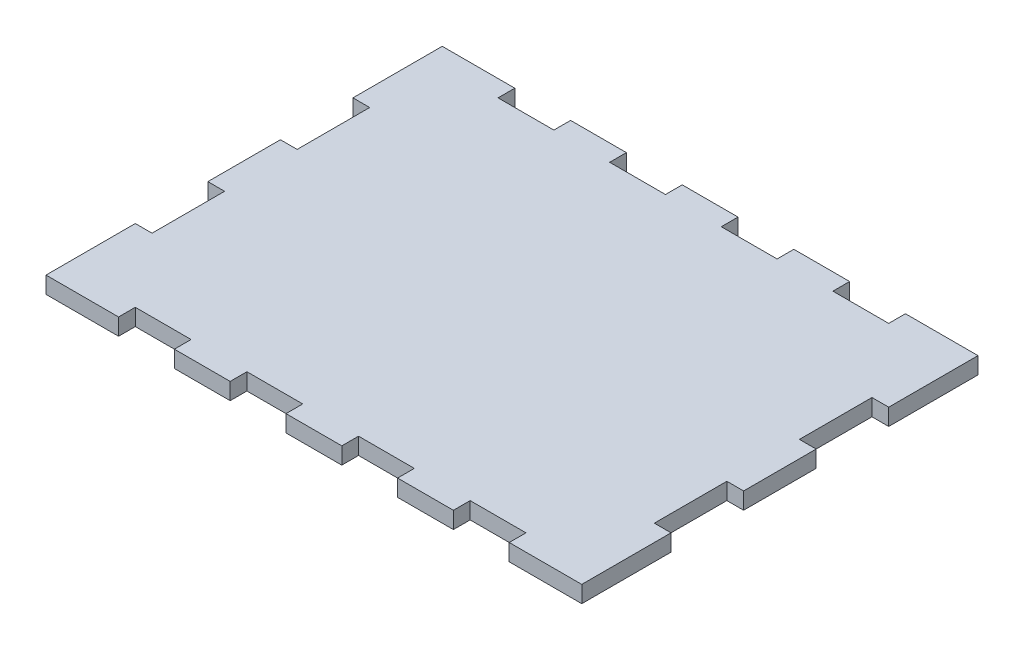
SolidWorks part; units mm, degrees
ref_plane "Front Plane" through (0, 0, 0) normal (0, 0, 1) x (1, 0, 0)
ref_plane "Top Plane" through (0, 0, 0) normal (0, 1, 0) x (1, 0, 0)
ref_plane "Right Plane" through (0, 0, 0) normal (1, 0, 0) x (0, 0, -1)
sketch "Sketch1" plane through (0, 0, 0) normal (0, 1, 0) x (1, 0, 0)
  line L0 (-70, 71) -> (-70, 65)
  line L1 (-96, -71) -> (-70, -71)
  line L2 (-96, -71) -> (-96, -39)
  line L3 (-96, 71) -> (-70, 71)
  line L4 (96, -71) -> (96, -39)
  line L5 (-96, -71) -> (96, 71) construction
  line L6 (-96, 71) -> (96, -71) construction
  line L11 (-90, -66.5625) -> (90, 66.5625) construction
  line L12 (-90, 66.5625) -> (90, -66.5625) construction
  line L13 (-90, -65) -> (-87.8873, -65)
  line L14 (-90, -39) -> (-90, -13)
  line L15 (-90, 65) -> (-87.8873, 65)
  line L16 (90, -39) -> (90, -13)
  line L17 (-90, -65) -> (90, 65) construction
  line L18 (-90, 65) -> (90, -65) construction
  line L19 (-50, 71) -> (-50, 65)
  line L20 (-30, 71) -> (-30, 65)
  line L21 (-10, 71) -> (-10, 65)
  line L22 (10, 71) -> (10, 65)
  line L23 (30, 71) -> (30, 65)
  line L24 (50, 71) -> (50, 65)
  line L25 (70, 71) -> (70, 65)
  line L26 (-50, 71) -> (-30, 71)
  line L27 (-10, 71) -> (10, 71)
  line L28 (30, 71) -> (50, 71)
  line L29 (70, 71) -> (96, 71)
  line L30 (-70, 65) -> (-50, 65)
  line L31 (-30, 65) -> (-10, 65)
  line L32 (10, 65) -> (30, 65)
  line L33 (50, 65) -> (70, 65)
  line L34 (87.8873, 65) -> (90, 65)
  line L35 (-105.6, 0) -> (105.6, 0) construction
  line L36 (87.8873, -65) -> (90, -65)
  line L37 (50, -65) -> (70, -65)
  line L38 (10, -65) -> (30, -65)
  line L39 (-30, -65) -> (-10, -65)
  line L40 (-70, -65) -> (-50, -65)
  line L41 (70, -71) -> (96, -71)
  line L42 (30, -71) -> (50, -71)
  line L43 (-10, -71) -> (10, -71)
  line L44 (-50, -71) -> (-30, -71)
  line L45 (70, -71) -> (70, -65)
  line L46 (50, -71) -> (50, -65)
  line L47 (30, -71) -> (30, -65)
  line L48 (10, -71) -> (10, -65)
  line L49 (-10, -71) -> (-10, -65)
  line L50 (-30, -71) -> (-30, -65)
  line L51 (-50, -71) -> (-50, -65)
  line L52 (-90, -65) -> (-87.8873, -65)
  line L53 (-96, -71) -> (-70, -71)
  line L54 (-70, -71) -> (-70, -65)
  line L55 (-50, -71) -> (-30, -71)
  line L56 (-70, -65) -> (-50, -65)
  line L57 (-30, -65) -> (-10, -65)
  line L58 (-10, -71) -> (10, -71)
  line L59 (10, -65) -> (30, -65)
  line L60 (30, -71) -> (50, -71)
  line L62 (70, -71) -> (96, -71)
  line L63 (-96, -39) -> (-90, -39)
  line L64 (-96, -13) -> (-90, -13)
  line L65 (-96, 13) -> (-90, 13)
  line L66 (-96, 39) -> (-90, 39)
  line L67 (-96, 39) -> (-96, 71)
  line L68 (-96, -13) -> (-96, 13)
  line L69 (-90, 13) -> (-90, 39)
  line L70 (0, -78.1) -> (0, 78.1) construction
  line L71 (90, 13) -> (90, 39)
  line L72 (96, -13) -> (96, 13)
  line L73 (96, 39) -> (96, 71)
  line L74 (96, 39) -> (90, 39)
  line L75 (96, 13) -> (90, 13)
  line L76 (96, -13) -> (90, -13)
  line L77 (96, -39) -> (90, -39)
  line L78 (90, -39) -> (90, -13)
  line L79 (96, -71) -> (96, -39)
  line L80 (96, 39) -> (96, 71)
  line L81 (90, 13) -> (90, 39)
  line L82 (96, -13) -> (96, 13)
  point P0 (0, 0)
  point P6 (0, 0)
  point P11 (0, 0)
  dimension "D1" = 192
  dimension "D2" = 142
  dimension "D3" = 130
  dimension "D4" = 180
  dimension "D5" = 26
  dimension "D6" = 20
  dimension "D7" = 20
  dimension "D8" = 20
  dimension "D9" = 20
  dimension "D10" = 20
  dimension "D11" = 20
  dimension "D12" = 20
  dimension "D13" = 32
  dimension "D14" = 26
  dimension "D15" = 26
  dimension "D16" = 26
  dimension "D17" = 6
extrude "Boss-Extrude1" add sketch "Sketch1" along normal blind 6
